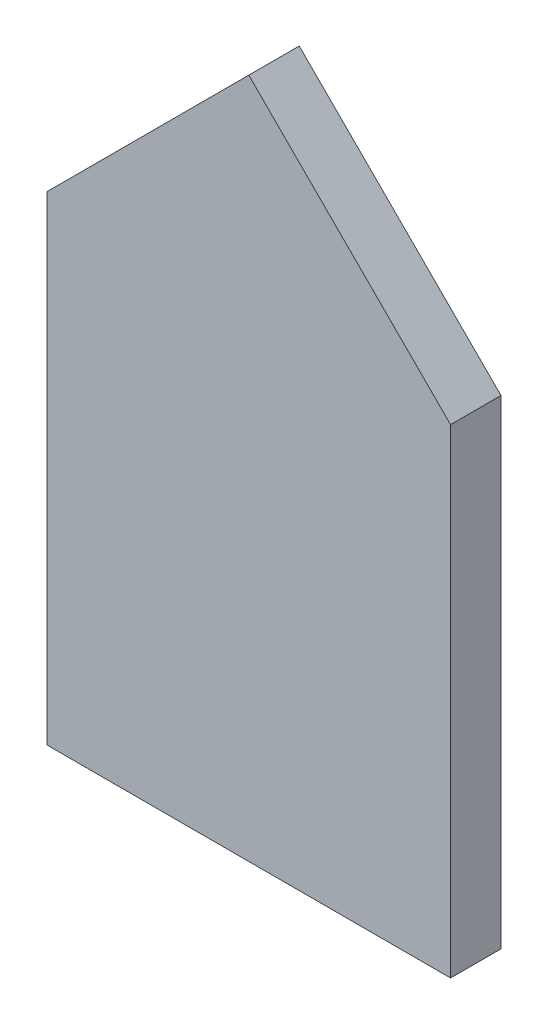
SolidWorks part; units mm, degrees
ref_plane "Plan de face" through (0, 0, 0) normal (0, 0, 1) x (1, 0, 0)
ref_plane "Plan de dessus" through (0, 0, 0) normal (0, 1, 0) x (1, 0, 0)
ref_plane "Plan de droite" through (0, 0, 0) normal (1, 0, 0) x (0, 0, -1)
sketch "Esquisse2" plane through (0, 0, 0) normal (0, 0, 1) x (1, 0, 0)
  line L0 (-0.4524, 79.7768) -> (-55.1492, 25.0799) construction
  line L1 (-40.4524, -55.2232) -> (39.5476, -55.2232)
  line L2 (-40.4524, -55.2232) -> (-40.4524, 79.7768) construction
  line L3 (-40.4524, 79.7768) -> (39.5476, 79.7768) construction
  line L4 (39.5476, -55.2232) -> (39.5476, 79.7768) construction
  line L5 (-40.4524, -55.2232) -> (39.5476, 79.7768) construction
  line L6 (-40.4524, 79.7768) -> (39.5476, -55.2232) construction
  line L7 (-40.4524, -55.2232) -> (-40.4524, 39.7768)
  line L8 (-40.4524, 39.7768) -> (-0.4524, 79.7768)
  line L9 (-0.4524, 79.7768) -> (39.5476, 39.7768)
  line L10 (39.5476, 39.7768) -> (39.5476, -55.2232)
  point P0 (-0.4524, 12.2768)
  dimension "D1" = 135
  dimension "D2" = 80
  dimension "D3" = 45
  dimension "D4" = 95
  dimension "D5" = 95
  dimension "D6" = 45
sketch "Esquisse3" plane through (0, 0, 0) normal (0, 0, 1) x (1, 0, 0)
extrude "Boss.-Extru.1" add sketch "Esquisse2" along normal blind 10 contours L8 L9 L10 L1 L7
